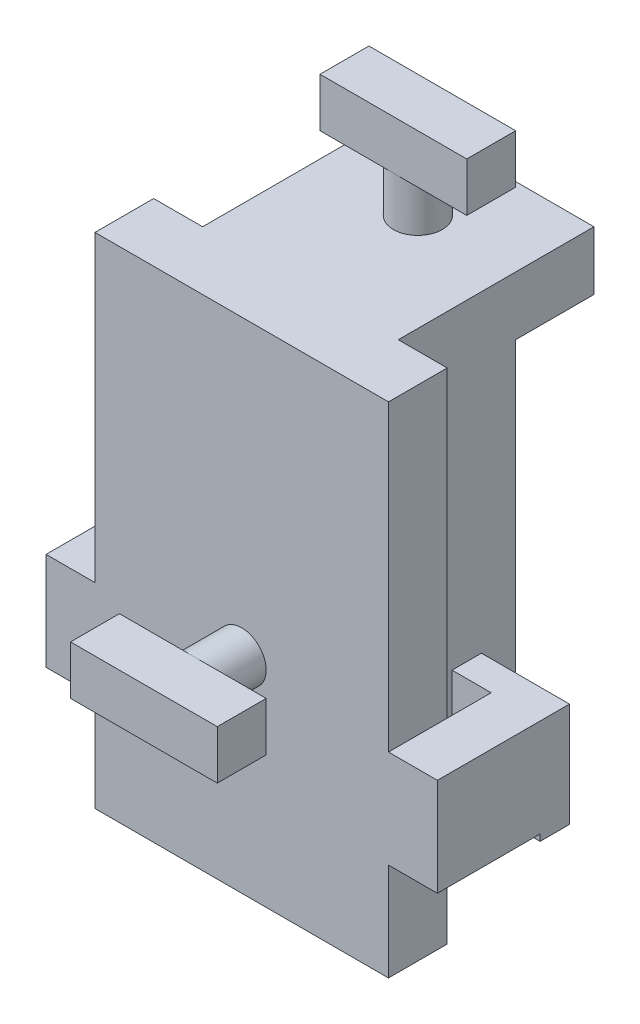
SolidWorks part; units mm, degrees
ref_plane "正面" through (0, 0, 0) normal (0, 0, 1) x (1, 0, 0)
ref_plane "平面" through (0, 0, 0) normal (0, 1, 0) x (1, 0, 0)
ref_plane "右側面" through (0, 0, 0) normal (1, 0, 0) x (0, 0, -1)
sketch "ｽｹｯﾁ1" plane through (0, 0, 0) normal (0, 0, 1) x (1, 0, 0)
  line L1 (0, 0) -> (20, 0)
  line L2 (0, 0) -> (0, 45)
  line L3 (0, 45) -> (20, 45)
  line L4 (20, 0) -> (20, 45)
  dimension "D1" = 45
  dimension "D2" = 20
extrude "ﾎﾞｽ - 押し出し1" add sketch "ｽｹｯﾁ1" along normal blind 12
sketch "ｽｹｯﾁ2" plane through (0, 45, 0) normal (0, 1, 0) x (1, 0, 0)
  line L1 (0, -12) -> (20, -12)
  line L2 (0, -12) -> (0, 8)
  line L3 (0, 8) -> (20, 8)
  line L4 (20, -12) -> (20, 8)
  circle A0 centre (10, 5) radius 1.5
  dimension "D2" = 3
  dimension "D1" = 20
  dimension "D3" = 17
  dimension "D4" = 10
extrude "ﾎﾞｽ - 押し出し2" add sketch "ｽｹｯﾁ2" along normal blind 6
sketch "ｽｹｯﾁ3" plane through (20, 0, 0) normal (1, 0, 0) x (0, 0, -1)
  line L0 (-12, 0) -> (0, 0) construction
  line L1 (0, 0) -> (0, 45) construction
  circle A0 centre (-3, 5) radius 1.5
  dimension "D1" = 3
  dimension "D2" = 5
  dimension "D3" = 3
extrude "ｶｯﾄ - 押し出し1" cut sketch "ｽｹｯﾁ3" against normal through all both and the other way through all
sketch "ｽｹｯﾁ4" plane through (0, 0, 12) normal (0, 0, 1) x (1, 0, 0)
  line L0 (0, 51) -> (20, 51) construction
  line L1 (-5, 51) -> (25, 51)
  line L2 (-5, 51) -> (-5, 0)
  line L3 (-5, 0) -> (25, 0)
  line L4 (25, 51) -> (25, 0)
  line L5 (0, 0) -> (20, 0) construction
  dimension "D1" = 5
  dimension "D2" = 5
extrude "ﾎﾞｽ - 押し出し3" add sketch "ｽｹｯﾁ4" along normal blind 6
sketch "ｽｹｯﾁ5" plane through (25, 0, 0) normal (1, 0, 0) x (0, 0, -1)
  line L0 (-18, 0) -> (-18, 51) construction
  line L1 (-18, 20) -> (-7.5, 20)
  line L2 (-18, 20) -> (-18, 10)
  line L3 (-18, 10) -> (-7.5, 10)
  line L4 (-7.5, 20) -> (-7.5, 10)
  line L6 (-18, 0) -> (-12, 0) construction
  dimension "D1" = 10
  dimension "D2" = 10.5
  dimension "D3" = 10
extrude "ﾎﾞｽ - 押し出し4" add sketch "ｽｹｯﾁ5" along normal blind 5
sketch "ｽｹｯﾁ6" plane through (0, 0, 7.5) normal (0, 0, -1) x (-1, 0, 0)
  line L1 (-30, 20) -> (-21, 20)
  line L2 (-30, 20) -> (-30, 9.3416)
  line L3 (-30, 9.3416) -> (-21, 9.3416)
  line L4 (-21, 20) -> (-21, 9.3416)
  dimension "D1" = 9
extrude "ﾎﾞｽ - 押し出し5" add sketch "ｽｹｯﾁ6" along normal blind 3
sketch "ｽｹｯﾁ7" plane through (-5, 0, 0) normal (-1, 0, 0) x (0, 0, 1)
  line L0 (18, 51) -> (18, 0) construction
  line L1 (18, 10) -> (7.5, 10)
  line L2 (18, 10) -> (18, 20)
  line L3 (18, 20) -> (7.5, 20)
  line L4 (7.5, 10) -> (7.5, 20)
  line L5 (18, 0) -> (12, 0) construction
  dimension "D1" = 10.5
  dimension "D2" = 10
  dimension "D3" = 10
extrude "ﾎﾞｽ - 押し出し6" add sketch "ｽｹｯﾁ7" along normal blind 5 contours L3 L4 L1 L2
sketch "ｽｹｯﾁ8" plane through (0, 0, 7.5) normal (0, 0, -1) x (-1, 0, 0)
  line L1 (10, 10) -> (1, 10)
  line L2 (10, 10) -> (10, 20.1449)
  line L3 (10, 20.1449) -> (1, 20.1449)
  line L4 (1, 10) -> (1, 20.1449)
  dimension "D1" = 9
extrude "ﾎﾞｽ - 押し出し7" add sketch "ｽｹｯﾁ8" along normal blind 3
sketch "ｽｹｯﾁ9" plane through (0, 51, 0) normal (0, 1, 0) x (1, 0, 0)
  line L0 (20, 8) -> (0, 8) construction
  line L1 (20, -12) -> (20, 8) construction
  circle A0 centre (10, 0) radius 2.5
  point P4 (0, 0)
  point P6 (2.0998, -0.0979)
  dimension "D1" = 5
  dimension "D2" = 8
  dimension "D3" = 10
extrude "ﾎﾞｽ - 押し出し8" add sketch "ｽｹｯﾁ9" along normal blind 10
sketch "ｽｹｯﾁ10" plane through (0, 61, 0) normal (0, 1, 0) x (1, 0, 0)
  line L0 (20, -12) -> (20, 8) construction
  line L1 (17.5, 2.5) -> (2.5, 2.5)
  line L2 (17.5, 2.5) -> (17.5, -2.5)
  line L3 (17.5, -2.5) -> (2.5, -2.5)
  line L4 (2.5, 2.5) -> (2.5, -2.5)
  line L5 (20, 8) -> (0, 8) construction
  dimension "D1" = 5
  dimension "D2" = 15
  dimension "D3" = 2.5
  dimension "D4" = 5.5
extrude "ﾎﾞｽ - 押し出し9" add sketch "ｽｹｯﾁ10" against normal blind 5
sketch "ｽｹｯﾁ11" plane through (0, 0, 18) normal (0, 0, 1) x (1, 0, 0)
  line L0 (25, 51) -> (-5, 51) construction
  line L1 (-5, 51) -> (-5, 20) construction
  circle A0 centre (10, 21) radius 2.5
  dimension "D3" = 5
  dimension "D1" = 30
  dimension "D2" = 15
extrude "ﾎﾞｽ - 押し出し10" add sketch "ｽｹｯﾁ11" along normal blind 10
sketch "ｽｹｯﾁ12" plane through (0, 0, 28) normal (0, 0, 1) x (1, 0, 0)
  line L0 (25, 20) -> (25, 51) construction
  line L1 (2.5, 23.5) -> (17.5, 23.5)
  line L2 (2.5, 23.5) -> (2.5, 18.5)
  line L3 (2.5, 18.5) -> (17.5, 18.5)
  line L4 (17.5, 23.5) -> (17.5, 18.5)
  line L5 (25, 51) -> (-5, 51) construction
  dimension "D1" = 5
  dimension "D2" = 15
  dimension "D3" = 7.5
  dimension "D4" = 27.5
extrude "ﾎﾞｽ - 押し出し11" add sketch "ｽｹｯﾁ12" against normal blind 5
